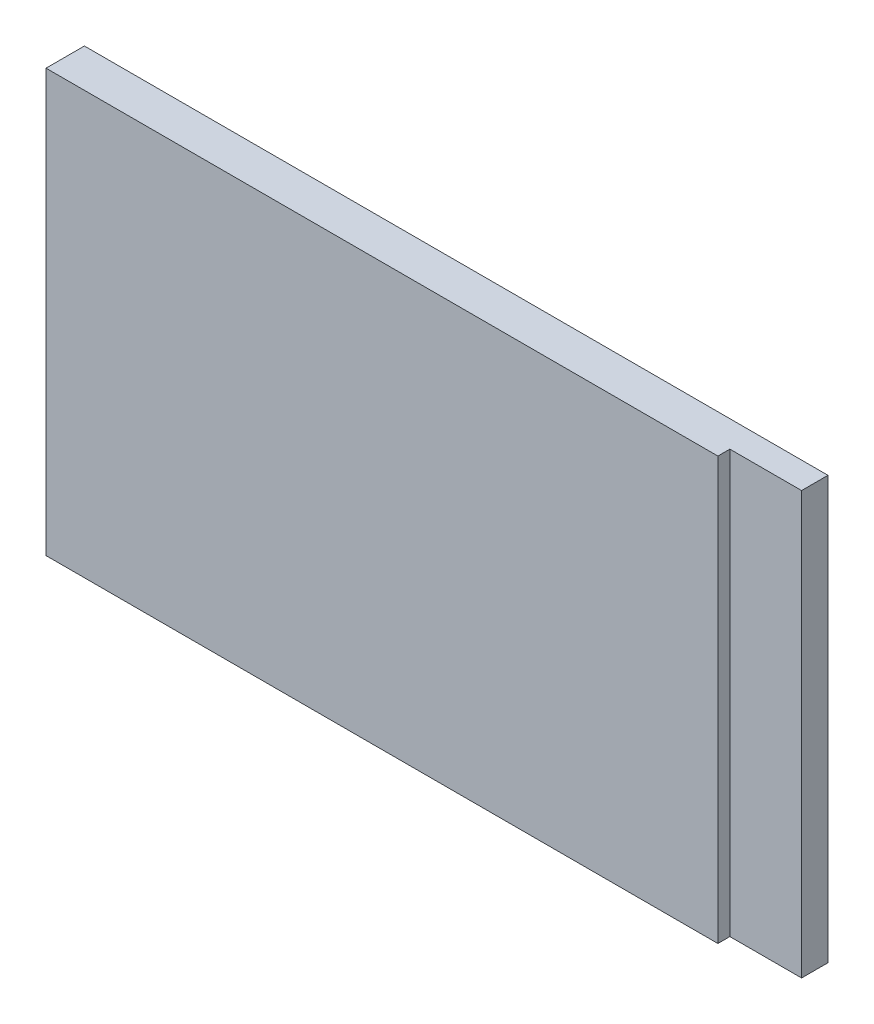
SolidWorks part; units mm, degrees
ref_plane "前视基准面" through (0, 0, 0) normal (0, 0, 1) x (1, 0, 0)
ref_plane "上视基准面" through (0, 0, 0) normal (0, 1, 0) x (1, 0, 0)
ref_plane "右视基准面" through (0, 0, 0) normal (1, 0, 0) x (0, 0, -1)
sketch "草图1" plane through (0, 0, 0) normal (0, 0, 1) x (1, 0, 0)
  line L1 (-15.5, 8.8) -> (15.5, 8.8)
  line L2 (-15.5, 8.8) -> (-15.5, -8.8)
  line L3 (-15.5, -8.8) -> (15.5, -8.8)
  line L4 (15.5, 8.8) -> (15.5, -8.8)
  line L5 (-15.5, 8.8) -> (15.5, -8.8) construction
  line L6 (-15.5, -8.8) -> (15.5, 8.8) construction
  point P0 (0, 0)
  dimension "D1" = 31
  dimension "D2" = 17.6
extrude "凸台-拉伸1" add sketch "草图1" along normal blind 1.6 contours L1 L4 L3 L2
sketch "草图2" plane through (0, 0, 1.6) normal (0, 0, 1) x (1, 0, 0)
  line L0 (-15.5, -8.8) -> (15.5, -8.8) construction
  line L1 (15.5, 8.8) -> (12.51, 8.8)
  line L2 (15.5, 8.8) -> (15.5, -8.8)
  line L3 (15.5, -8.8) -> (12.51, -8.8)
  line L4 (12.51, 8.8) -> (12.51, -8.8)
  dimension "D1" = 2.99
extrude "切除-拉伸1" cut sketch "草图2" against normal blind 0.5 contours L4 L3 L2 L1
